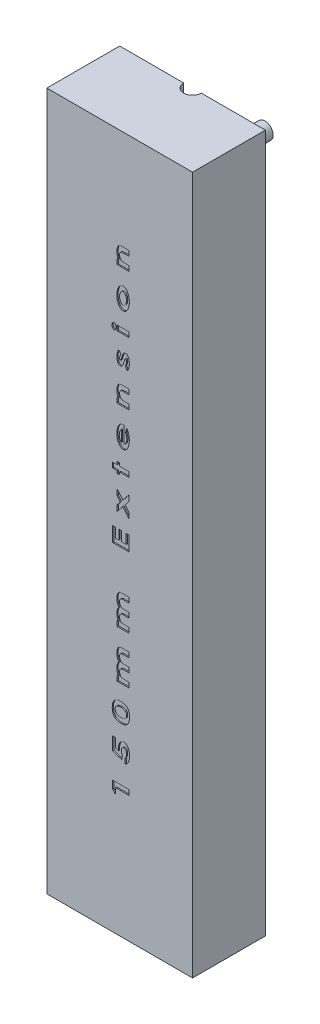
SolidWorks part; units mm, degrees
ref_plane "Front Plane" through (0, 0, 0) normal (0, 0, 1) x (1, 0, 0)
ref_plane "Top Plane" through (0, 0, 0) normal (0, 1, 0) x (1, 0, 0)
ref_plane "Right Plane" through (0, 0, 0) normal (1, 0, 0) x (0, 0, -1)
sketch "Sketch1" plane through (0, 0, 0) normal (0, 1, 0) x (1, 0, 0)
  circle A0 centre (0, 0) radius 12.5
  dimension "D1" = 25
extrude "Boss-Extrude1" add sketch "Sketch1" along normal blind 150.5
sketch "Sketch2" plane through (0, 150.5, 0) normal (0, 1, 0) x (1, 0, 0)
  line L1 (-13.5, 0) -> (13.5, 0)
  arc A0 (-13.5, 0) -> (13.5, 0) centre (0, 0) ccw
  dimension "D1" = 13.5
  dimension "D2" = 13.5
extrude "Boss-Extrude2" add sketch "Sketch2" against normal blind 148.5
sketch "Sketch8" plane through (0, 150.5, 0) normal (0, 1, 0) x (1, 0, 0)
  circle A0 centre (0, 0) radius 12.5
  dimension "D1" = 25
extrude "Cut-Extrude2" cut sketch "Sketch8" against normal through all
sketch "Sketch9" plane through (0, 150.5, 0) normal (0, 1, 0) x (1, 0, 0)
  line L0 (12.5, 0) -> (1.875, 0)
  line L1 (-1.875, 0) -> (-12.5, 0)
  arc A0 (-1.875, 0) -> (1.875, 0) centre (0, 0) ccw
  arc A1 (-12.5, 0) -> (12.5, 0) centre (0, 0) ccw
  dimension "D1" = 3.75
extrude "Boss-Extrude7" add sketch "Sketch9" against normal blind 8
sketch "Sketch11" plane through (0, 2, 0) normal (0, -1, 0) x (1, 0, 0)
  line L0 (-12.5, 0) -> (-8, 0)
  line L1 (8, 0) -> (12.5, 0)
  arc A0 (8, 0) -> (-8, 0) centre (0, 0) ccw
  arc A1 (12.5, 0) -> (-12.5, 0) centre (0, 0) ccw
  dimension "D1" = 16
extrude "Boss-Extrude8" add sketch "Sketch11" against normal blind 121
sketch "Sketch12" plane through (0, 150.5, 0) normal (0, 1, 0) x (1, 0, 0)
  line L0 (-13.5, 0) -> (-15.5, 0)
  line L1 (13.5, 0) -> (15.5, 0)
  line L3 (-15.5, 0) -> (-15.5, -15.5)
  line L4 (-15.5, -15.5) -> (15.5, -15.5)
  line L5 (15.5, -15.5) -> (15.5, 0)
  arc A2 (-13.5, 0) -> (13.5, 0) centre (0, 0) ccw
  dimension "D1" = 2
  dimension "D3" = 2
extrude "Boss-Extrude9" add sketch "Sketch12" against normal blind 148.5
sketch "Sketch13" plane through (0, 0, 0) normal (0, 0, -1) x (-1, 0, 0)
  line L0 (15.5, 2) -> (15.5, 150.5) construction
  line L1 (1.875, 150.5) -> (15.5, 150.5) construction
  circle A0 centre (12, 147) radius 1.75
  dimension "D1" = 3.5
  dimension "D2" = 3.5
  dimension "D3" = 3.5
extrude "Cut-Extrude3" cut sketch "Sketch13" against normal blind 3.5
sketch "Sketch14" plane through (0, 0, 0) normal (0, 0, -1) x (-1, 0, 0)
  line L0 (-15.5, 2) -> (-15.5, 150.5) construction
  line L1 (-15.5, 150.5) -> (-1.875, 150.5) construction
  circle A0 centre (-12, 147) radius 1.75
  dimension "D1" = 3.5
  dimension "D2" = 3.5
  dimension "D3" = 3.5
extrude "Boss-Extrude10" add sketch "Sketch14" along normal blind 3.4
sketch "Sketch15" plane through (0, 0, 0) normal (0, 0, -1) x (-1, 0, 0)
  line L0 (-15.5, 2) -> (-15.5, 150.5) construction
  line L1 (-15.5, 2) -> (-8, 2) construction
  circle A0 centre (-12, 5.5) radius 1.75
  dimension "D1" = 3.5
  dimension "D2" = 3.5
  dimension "D3" = 3.5
extrude "Cut-Extrude4" cut sketch "Sketch15" against normal blind 3.5
sketch "Sketch16" plane through (0, 0, 0) normal (0, 0, -1) x (-1, 0, 0)
  line L0 (15.5, 2) -> (15.5, 150.5) construction
  line L1 (8, 2) -> (15.5, 2) construction
  circle A0 centre (12, 5.5) radius 1.75
  dimension "D1" = 3.5
  dimension "D3" = 3.5
  dimension "D2" = 3.5
extrude "Boss-Extrude11" add sketch "Sketch16" along normal blind 3.4
sketch "Sketch18" plane through (0, 0, 15.5) normal (0, 0, 1) x (1, 0, 0)
  text T0 "<b>150mm Extension</b>" font "Century Gothic" height 3.5
  point P7 (-0.5, 130.0026)
extrude "Cut-Extrude6" cut sketch "Sketch18" against normal blind 0.25
